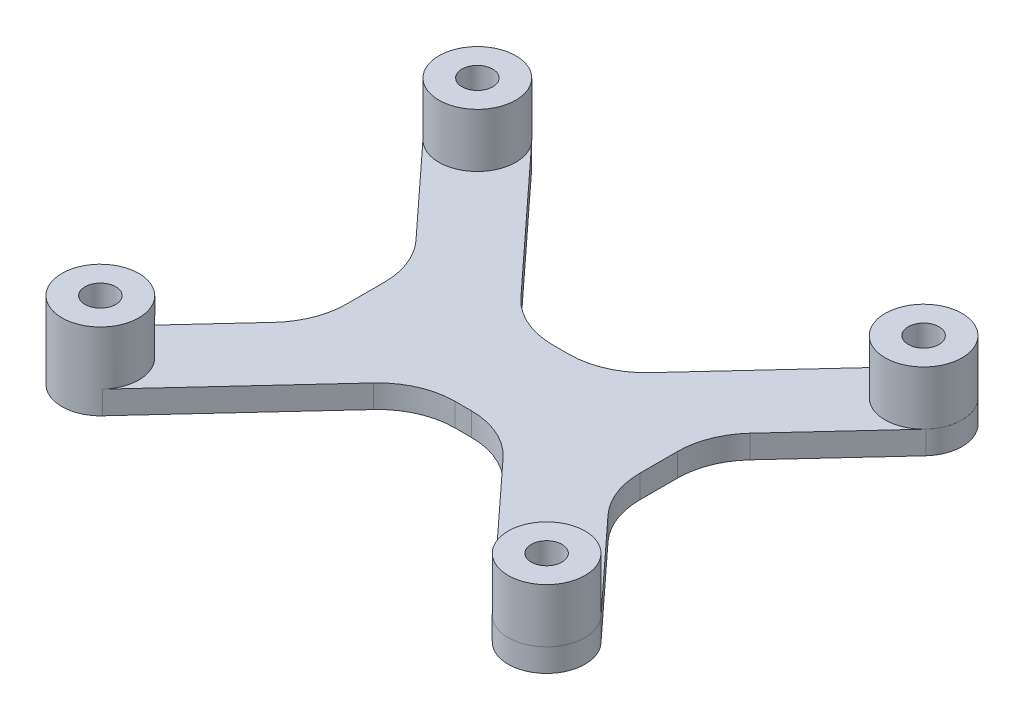
SolidWorks part; units mm, degrees
ref_plane "Front Plane" through (0, 0, 0) normal (0, 0, 1) x (1, 0, 0)
ref_plane "Top Plane" through (0, 0, 0) normal (0, 1, 0) x (1, 0, 0)
ref_plane "Right Plane" through (0, 0, 0) normal (1, 0, 0) x (0, 0, -1)
sketch "Sketch1" plane through (0, 0, 0) normal (0, 1, 0) x (1, 0, 0)
  line L1 (-29, -24.5) -> (29, -24.5) construction
  line L2 (-29, -24.5) -> (-29, 24.5) construction
  line L3 (-29, 24.5) -> (29, 24.5) construction
  line L4 (29, -24.5) -> (29, 24.5) construction
  line L5 (-29, -24.5) -> (29, 24.5) construction
  line L6 (-29, 24.5) -> (29, -24.5) construction
  point P0 (0, 0)
  dimension "D1" = 49
  dimension "D2" = 58
sketch "Sketch2" plane through (0, 0, 0) normal (0, 1, 0) x (1, 0, 0)
  circle A0 centre (-29, 24.5) radius 5
  circle A2 centre (-29, -24.5) radius 5
  circle A3 centre (29, 24.5) radius 5
  circle A4 centre (29, -24.5) radius 5
  dimension "D1" = 10
  dimension "D2" = 10
  dimension "D3" = 10
  dimension "D4" = 10
extrude "Boss-Extrude1" add sketch "Sketch2" along normal blind 7
sketch "Sketch3" plane through (0, 7, 0) normal (0, 1, 0) x (1, 0, 0)
  circle A0 centre (-29, 24.5) radius 2
  circle A1 centre (-29, -24.5) radius 2
  circle A2 centre (29, -24.5) radius 2
  circle A3 centre (29, 24.5) radius 2
  dimension "D1" = 4
  dimension "D2" = 4
  dimension "D3" = 4
  dimension "D4" = 4
extrude "Cut-Extrude2" cut sketch "Sketch3" against normal blind 4.8
sketch "Sketch4" plane through (0, 0, 0) normal (0, 1, 0) x (1, 0, 0)
  line L1 (-19.05, -6.35) -> (19.05, -6.35)
  line L2 (-19.05, -6.35) -> (-19.05, 6.35)
  line L3 (-19.05, 6.35) -> (19.05, 6.35)
  line L4 (19.05, -6.35) -> (19.05, 6.35)
  line L5 (-19.05, -6.35) -> (19.05, 6.35) construction
  line L6 (-19.05, 6.35) -> (19.05, -6.35) construction
  point P0 (0, 0)
  dimension "D1" = 12.7
  dimension "D2" = 38.1
extrude "Boss-Extrude2" add sketch "Sketch4" against normal blind 3 separate body
sketch "Sketch5" plane through (0, 0, 0) normal (0, 1, 0) x (1, 0, 0)
  line L0 (-19.05, -6.35) -> (-32.6739, -21.1085)
  line L1 (-25.3261, -27.8915) -> (-5.4406, -6.35)
  line L2 (-19.05, -6.35) -> (19.05, -6.35) construction
  line L3 (-5.4406, -6.35) -> (-19.05, -6.35)
  circle A0 centre (-29, -24.5) radius 5 construction
  arc A1 (-25.3261, -27.8915) -> (-32.5599, -20.989) centre (-29, -24.5) cw
extrude "Boss-Extrude3" add sketch "Sketch5" against normal blind 3
mirror "Mirror3" about plane through (0, 0, 0) normal (1, 0, 0) of "Boss-Extrude3"
mirror "Mirror4" about plane through (0, 0, 0) normal (0, 0, 1) of "Mirror3", "Boss-Extrude3"
fillet "Fillet1" radius 10 8 edges at (-19.05, -1.5, 6.35) (-19.05, -1.5, -6.35) (-5.4406, -1.5, -6.35) (5.4406, -1.5, -6.35) (19.05, -1.5, -6.35) (19.05, -1.5, 6.35) (5.4406, -1.5, 6.35) (-5.4406, -1.5, 6.35)
